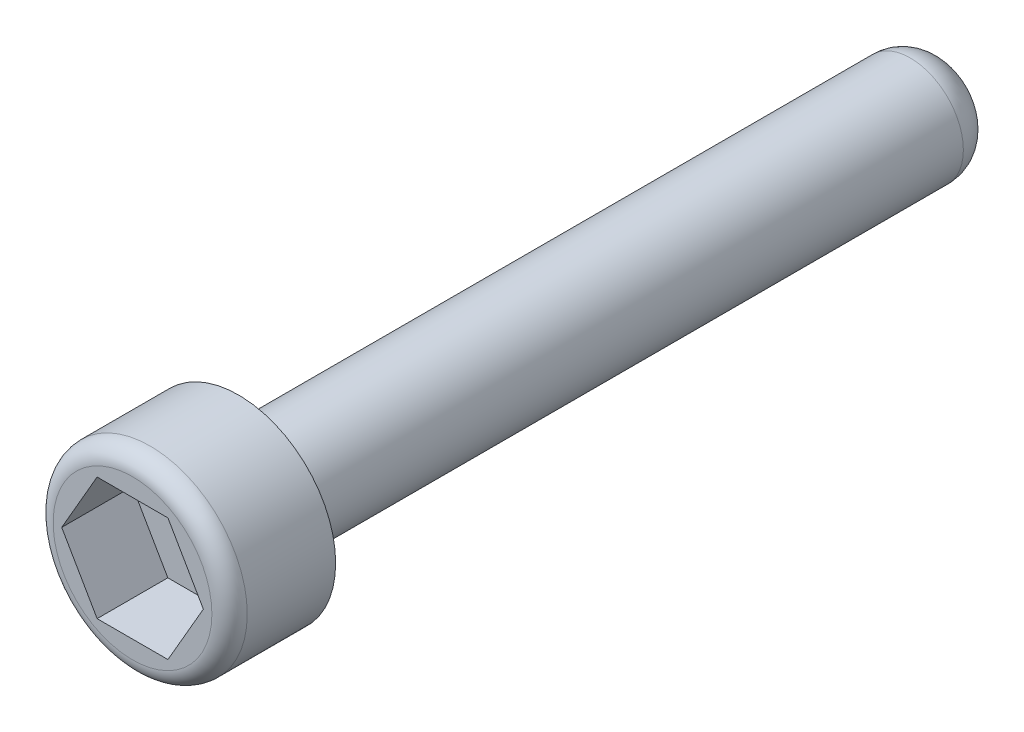
SolidWorks part; units mm, degrees
ref_plane "Front Plane" through (0, 0, 0) normal (0, 0, 1) x (1, 0, 0)
ref_plane "Top Plane" through (0, 0, 0) normal (0, 1, 0) x (1, 0, 0)
ref_plane "Right Plane" through (0, 0, 0) normal (1, 0, 0) x (0, 0, -1)
sketch "Sketch1" plane through (0, 0, 0) normal (0, 0, 1) x (1, 0, 0)
  circle A0 centre (0, 0) radius 1.5
extrude "Extrude1" add sketch "Sketch1" against normal blind 20
sketch "Sketch2" plane through (0, 0, 0) normal (0, 0, 1) x (1, 0, 0)
  circle A0 centre (0, 0) radius 2.745
extrude "Extrude2" add sketch "Sketch2" along normal blind 3
sketch "Sketch3" plane through (0, 0, 3) normal (0, 0, 1) x (1, 0, 0)
  line L1 (-2.0031, 0) -> (-1.0016, -1.7348)
  line L2 (-1.0016, -1.7348) -> (1.0016, -1.7348)
  line L3 (1.0016, -1.7348) -> (2.0031, 0)
  line L4 (2.0031, 0) -> (1.0016, 1.7348)
  line L5 (1.0016, 1.7348) -> (-1.0016, 1.7348)
  line L6 (-1.0016, 1.7348) -> (-2.0031, 0)
  circle A0 centre (0, 0) radius 1.7348 construction
extrude "Cut-Extrude1" cut sketch "Sketch3" against normal blind 2
fillet "Fillet1" radius 0.5 1 edges at (2.745, 0, 3)
fillet "Fillet2" radius 1 1 edges at (1.5, 0, -20)
